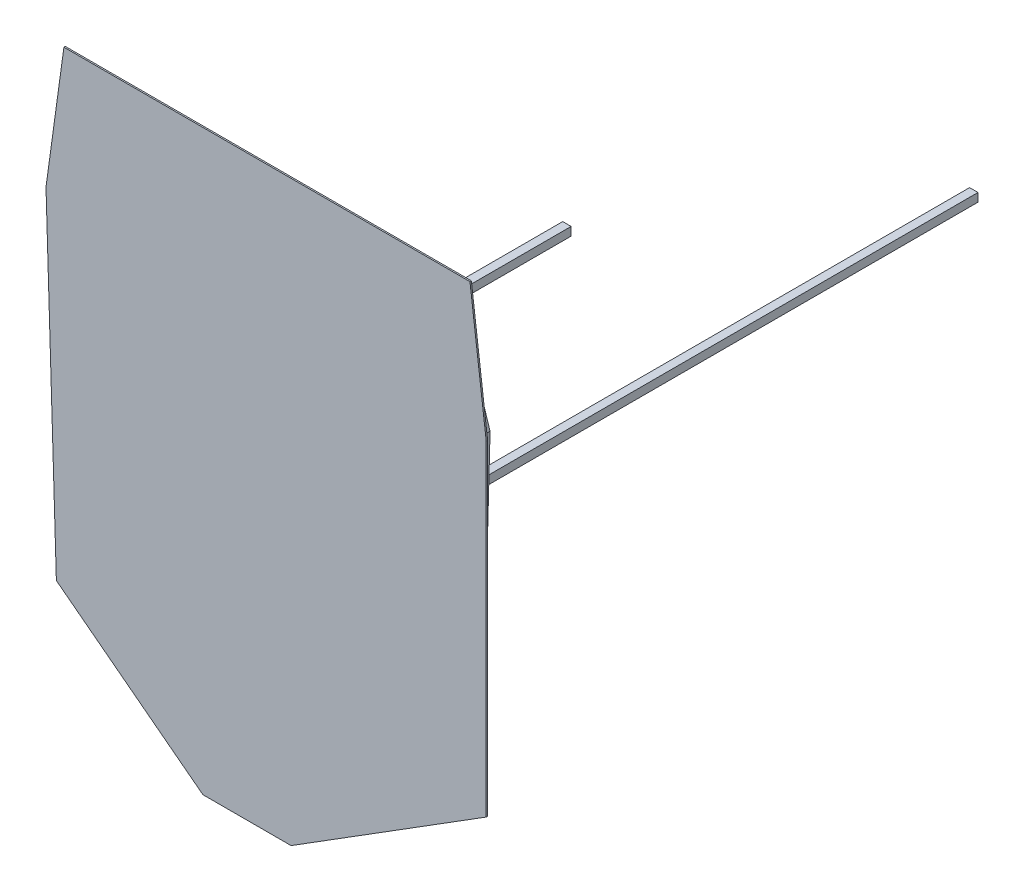
SolidWorks part; units mm, degrees
ref_plane "Front" through (0, 0, 0) normal (0, 0, 1) x (1, 0, 0)
ref_plane "Top" through (0, 0, 0) normal (0, 1, 0) x (1, 0, 0)
ref_plane "Right" through (0, 0, 0) normal (1, 0, 0) x (0, 0, -1)
sketch "Esquisse1" plane through (0, 0, 0) normal (0, 0, 1) x (1, 0, 0)
  line L1 (0, 0) -> (50, 0)
  line L2 (0, 0) -> (0, 50)
  line L3 (0, 50) -> (50, 50)
  line L4 (50, 0) -> (50, 50)
  dimension "D1" = 50
  dimension "D2" = 50
extrude "Boss.-Extru.1" add sketch "Esquisse1" along normal blind 5
sketch "Esquisse2" plane through (0, 0, 5) normal (0, 0, 1) x (1, 0, 0)
  line L0 (-17.1381, 66.75) -> (11.2464, 134.0009)
  line L1 (11.2464, 134.0009) -> (274.5644, 134.0009)
  line L2 (274.5644, 134.0009) -> (292.2191, 78.9632)
  line L3 (292.2191, 78.9632) -> (285.6582, -157.0934)
  line L4 (285.6582, -157.0934) -> (157.6257, -238.0143)
  line L5 (157.6257, -238.0143) -> (94.9951, -238.0143)
  line L6 (94.9951, -238.0143) -> (-5.3743, -157.0934)
  line L7 (-5.3743, -157.0934) -> (-17.1381, 66.75)
  point P2 (-9.1913, 79.1345)
  point P5 (6.2963, 129.1991)
  point P10 (261.7989, 129.522)
  point P11 (294.2875, 81.7228)
  point P12 (277.483, 129.522)
  point P13 (-9.1535, -167.9097)
  point P14 (284.5218, -167.9097)
  point P15 (158.5987, -253.3108)
  point P16 (96.3859, -249.3894)
  point P17 (0, 0)
  point P18 (156.8558, -247.6614)
  point P19 (-13.8181, 73.916)
  point P20 (92.2972, -242.8492)
  point P21 (160.5059, -246.1649)
  point P22 (-13.8051, -151.4306)
  point P23 (289.8182, -157.5884)
  point P24 (158.6112, -242.8492)
  point P25 (91.6696, -238.0143)
  point P26 (157.6257, -238.0143)
  point P27 (94.9951, -238.0143)
  point P28 (285.6582, -157.0934)
  point P29 (-11.9833, -157.0934)
  point P30 (11.2019, 133.8956)
  point P31 (274.5644, 134.0009)
  point P32 (292.2191, 78.9632)
  point P33 (-17.1381, -157.0934)
  point P34 (-5.3743, -157.0934)
extrude "Boss.-Extru.2" add sketch "Esquisse2" against normal up to vertex (5 mm away) up to point (0, 50, 0)
sketch "Esquisse3" plane through (0, 0, 0) normal (0, 0, -1) x (-1, 0, 0)
  line L0 (0, -121.7217) -> (6, -121.7217)
  line L1 (6, -121.7217) -> (6, -115.7217)
  line L2 (6, -115.7217) -> (0, -115.7217)
  line L4 (0, -115.7217) -> (0, -121.7217)
  line L6 (-284, 44.2389) -> (-290, 44.2389)
  line L7 (-284, 44.2389) -> (-284, 50.2389)
  line L8 (-284, 50.2389) -> (-290, 50.2389)
  line L9 (-290, 44.2389) -> (-290, 50.2389)
  dimension "D1" = 6
  dimension "D2" = 6
  dimension "D3" = 6
  dimension "D4" = 6
extrude "Boss.-Extru.3" add sketch "Esquisse3" along normal blind 350
sketch "Esquisse4" plane through (0, 0, 5) normal (0, 0, 1) x (1, 0, 0)
  line L0 (-5.5339, 170.1435) -> (283.89, 170.1435)
  line L1 (283.89, 170.1435) -> (295.4804, 77.4204)
  line L2 (295.4804, 77.4204) -> (295.4804, -154.5668)
  line L3 (295.4804, -154.5668) -> (156.3957, -241.7353)
  line L4 (156.3957, -241.7353) -> (93.5299, -241.7353)
  line L5 (93.5299, -241.7353) -> (-10.9091, -161.7784)
  line L6 (-10.9091, -161.7784) -> (-18.3001, 77.4204)
  line L7 (-18.3001, 77.4204) -> (-5.5339, 170.1435)
  point P2 (94.9951, -243.7511)
  point P9 (156.3957, -241.7353)
  point P10 (291.4489, -157.0934)
  point P11 (295.4804, 77.4204)
  point P12 (284.058, 168.7997)
  point P13 (-5.5339, 170.1435)
  point P14 (-23.6753, 67.3418)
  point P15 (-10.9091, -161.7784)
  point P16 (-18.3001, 77.4204)
extrude "Boss.-Extru.4" add sketch "Esquisse4" along normal blind 1
